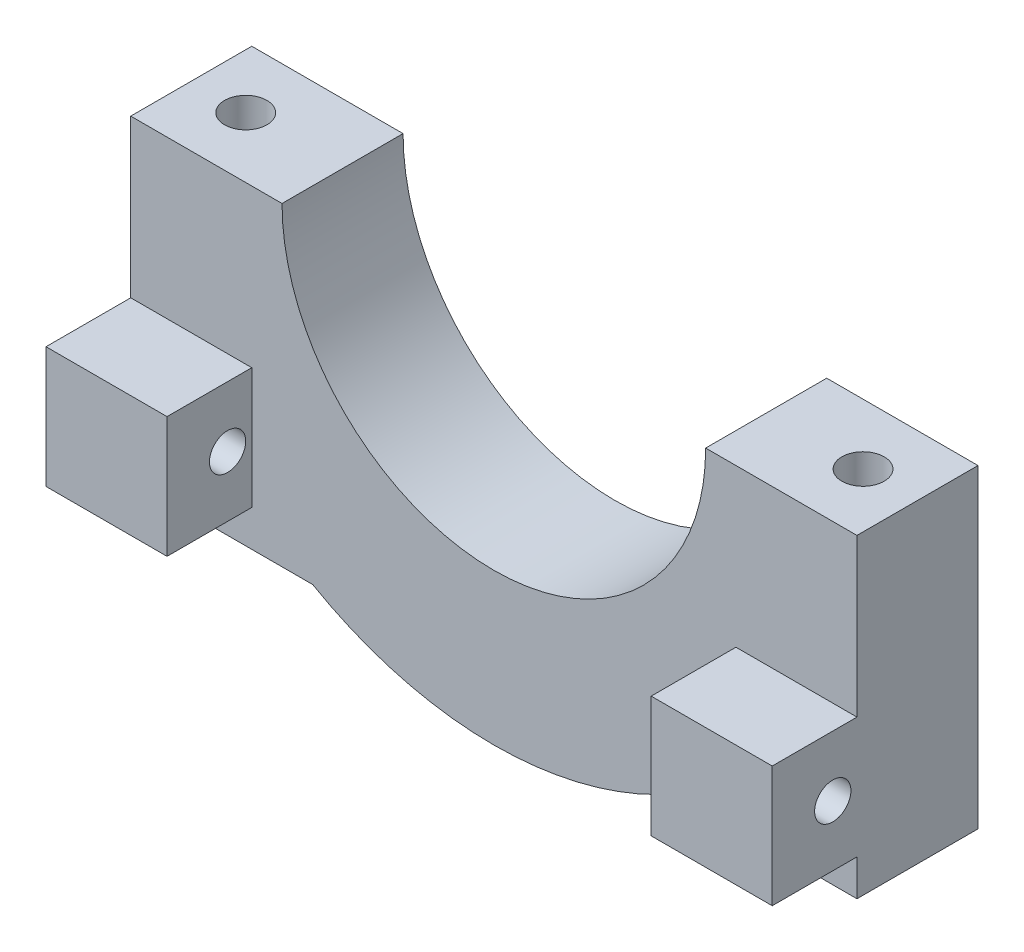
SolidWorks part; units mm, degrees
ref_plane "Ön Düzlem" through (0, 0, 0) normal (0, 0, 1) x (1, 0, 0)
ref_plane "Üst Düzlem" through (0, 0, 0) normal (0, 1, 0) x (1, 0, 0)
ref_plane "Sağ Düzlem" through (0, 0, 0) normal (1, 0, 0) x (0, 0, -1)
sketch "Çizim2" plane through (0, 0, 0) normal (0, 0, 1) x (1, 0, 0)
  line L0 (14.9666, -26) -> (30, -26)
  line L1 (-30, -26) -> (-14.9666, -26)
  line L2 (-30, -26) -> (-30, 0)
  line L4 (30, -26) -> (30, 0)
  line L16 (30, 0) -> (17.5, 0)
  line L17 (-17.5, 0) -> (-30, 0)
  arc A0 (-17.5, 0) -> (17.5, 0) centre (0, 0) ccw
  arc A1 (-14.9666, -26) -> (14.9666, -26) centre (0, 0) ccw
  dimension "D7" = 35
  dimension "D4" = 30
  dimension "D1" = 30
  dimension "D2" = 26
  dimension "D3" = 60
extrude "Yükseklik-Ekstrüzyon1" add sketch "Çizim2" along normal blind 10
sketch "Çizim7" plane through (0, 0, 0) normal (0, 1, 0) x (1, 0, 0)
  line L0 (30, -10) -> (30, 0) construction
  line L2 (30, -10) -> (17.5, -10) construction
  circle A0 centre (25.5, -5) radius 1.75
  dimension "D2" = 3.5
  dimension "D1" = 4.5
  dimension "D3" = 5
extrude "Kes-Ekstrüzyon3" cut sketch "Çizim7" against normal up to next
ref_plane "Düzlem1" through (0, 0, 0) normal (-1, 0, 0) x (0, 0, 1)
mirror "Aynalama1" about plane through (0, 0, 0) normal (-1, 0, 0) of "Kes-Ekstrüzyon3"
sketch "Sketch1" plane through (0, 0, 10) normal (0, 0, 1) x (1, 0, 0)
  line L1 (-30, -13) -> (-20, -13)
  line L2 (-30, -13) -> (-30, -23)
  line L3 (-30, -23) -> (-20, -23)
  line L4 (-20, -13) -> (-20, -23)
  line L5 (-17.5, 0) -> (-30, 0) construction
  line L6 (-30, 0) -> (-30, -26) construction
  dimension "D1" = 10
  dimension "D2" = 13
extrude "Boss-Extrude1" add sketch "Sketch1" along normal blind 7
sketch "Sketch2" plane through (-30, 0, 0) normal (-1, 0, 0) x (0, 0, 1)
  line L0 (17, -13) -> (10, -13) construction
  line L2 (17, -13) -> (17, -23) construction
  circle A0 centre (12, -18) radius 1.5
  dimension "D1" = 3
  dimension "D2" = 5
  dimension "D3" = 5
extrude "Cut-Extrude1" cut sketch "Sketch2" against normal up to next
mirror "Mirror1" about plane through (0, 0, 0) normal (1, 0, 0) of "Cut-Extrude1", "Boss-Extrude1"
